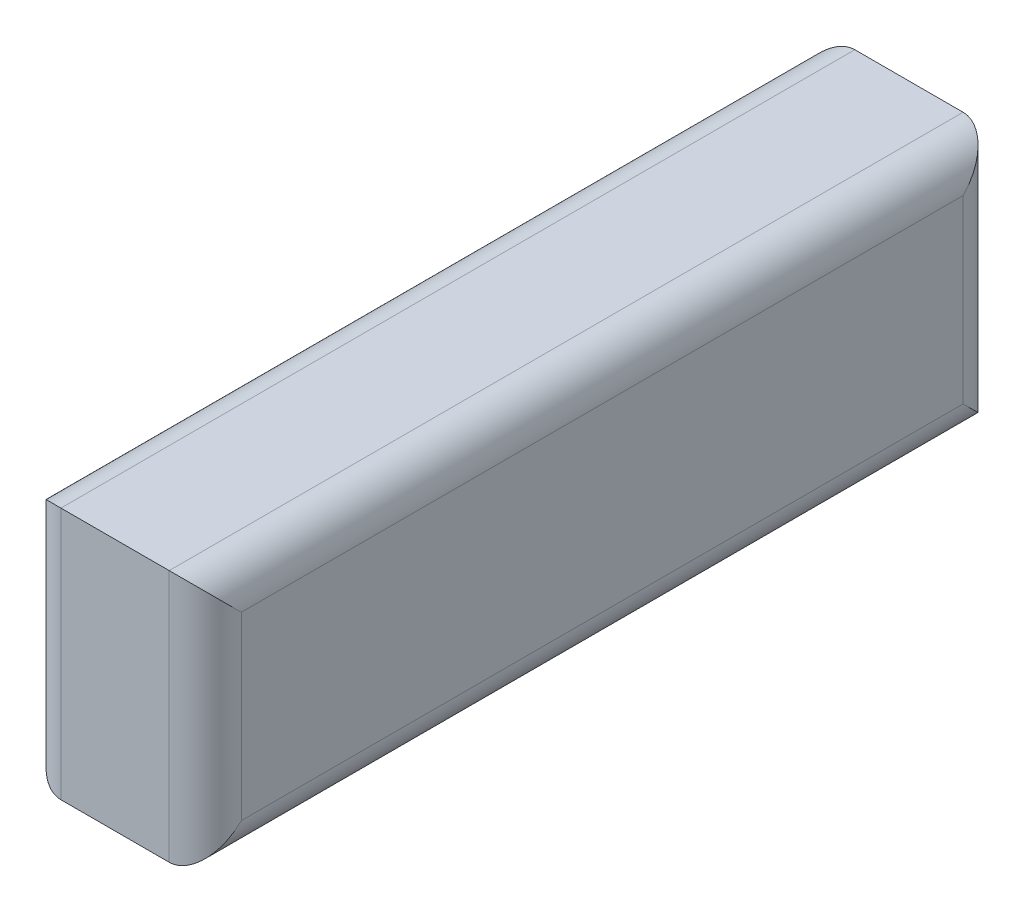
SolidWorks part; units mm, degrees
ref_plane "Front Plane" through (0, 0, 0) normal (0, 0, 1) x (1, 0, 0)
ref_plane "Top Plane" through (0, 0, 0) normal (0, 1, 0) x (1, 0, 0)
ref_plane "Right Plane" through (0, 0, 0) normal (1, 0, 0) x (0, 0, -1)
sketch "Sketch1" plane through (0, 0, 0) normal (0, 0, 1) x (1, 0, 0)
  line L1 (12.5, -17.5) -> (-12.5, -17.5)
  line L2 (12.5, -17.5) -> (12.5, 17.5)
  line L3 (12.5, 17.5) -> (-12.5, 17.5)
  line L4 (-12.5, -17.5) -> (-12.5, 17.5)
  line L5 (12.5, -17.5) -> (-12.5, 17.5) construction
  line L6 (12.5, 17.5) -> (-12.5, -17.5) construction
  point P0 (0, 0)
  dimension "D1" = 25
  dimension "D2" = 35
extrude "Boss-Extrude1" add sketch "Sketch1" along normal blind 110
fillet "Fillet1" radius 5 8 edges at (-12.5, 17.5, 55) (-12.5, 0, 110) (-12.5, -17.5, 55) (-12.5, 0, 0) (12.5, -17.5, 55) (12.5, 0, 110) (12.5, 17.5, 55) (12.5, 0, 0)
